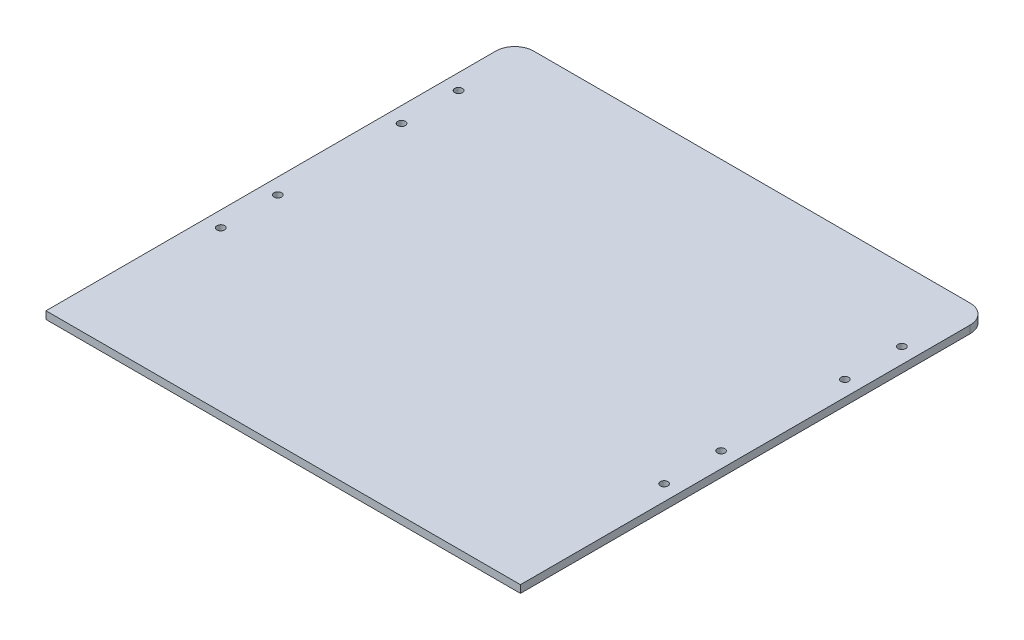
SolidWorks part; units mm, degrees
material "Medium density fiberboard, parallel to board"
ref_plane "Alzado" through (0, 0, 0) normal (0, 0, 1) x (1, 0, 0)
ref_plane "Planta" through (0, 0, 0) normal (0, 1, 0) x (1, 0, 0)
ref_plane "Vista lateral" through (0, 0, 0) normal (1, 0, 0) x (0, 0, -1)
sketch "Croquis1" plane through (0, 0, 0) normal (0, 1, 0) x (1, 0, 0)
  line L1 (-125, -123.5) -> (125, -123.5)
  line L2 (-125, -123.5) -> (-125, 113.5)
  line L3 (-115, 123.5) -> (115, 123.5)
  line L4 (125, -123.5) -> (125, 113.5)
  line L5 (-125, -123.5) -> (125, 123.5) construction
  line L6 (-125, 123.5) -> (125, -123.5) construction
  arc A0 (115, 123.5) -> (125, 113.5) centre (115, 113.5) cw
  arc A1 (-125, 113.5) -> (-115, 123.5) centre (-115, 113.5) cw
  point P0 (0, 0)
  dimension "D3" = 10
  dimension "D1" = 250
  dimension "D2" = 247
extrude "Saliente-Extruir1" add sketch "Croquis1" along normal mid plane 4
sketch "Croquis2" plane through (0, 2, 0) normal (0, 1, 0) x (1, 0, 0)
  line L0 (115, 123.5) -> (-115, 123.5) construction
  line L1 (-125, 113.5) -> (-125, -123.5) construction
  line L2 (-125, -123.5) -> (125, -123.5) construction
  line L3 (0, 48.6661) -> (0, -35.7913) construction
  circle A0 centre (-116.8, 85.7) radius 2
  circle A1 centre (-116.8, 55.65) radius 2
  circle A2 centre (-116.8, -9.5542) radius 2
  circle A3 centre (-116.8, -39.6) radius 2
  circle A4 centre (116.8, -39.6) radius 2
  circle A5 centre (116.8, -9.5542) radius 2
  circle A6 centre (116.8, 55.65) radius 2
  circle A7 centre (116.8, 85.7) radius 2
  dimension "D5" = 4
  dimension "D6" = 4
  dimension "D7" = 4
  dimension "D8" = 4
  dimension "D1" = 37.8
  dimension "D2" = 8.2
  dimension "D3" = 8.2
  dimension "D4" = 30.0458
  dimension "D9" = 8.2
  dimension "D10" = 83.9
  dimension "D11" = 30.05
  dimension "D12" = 8.2
extrude "Cortar-Extruir1" cut sketch "Croquis2" against normal blind 10
